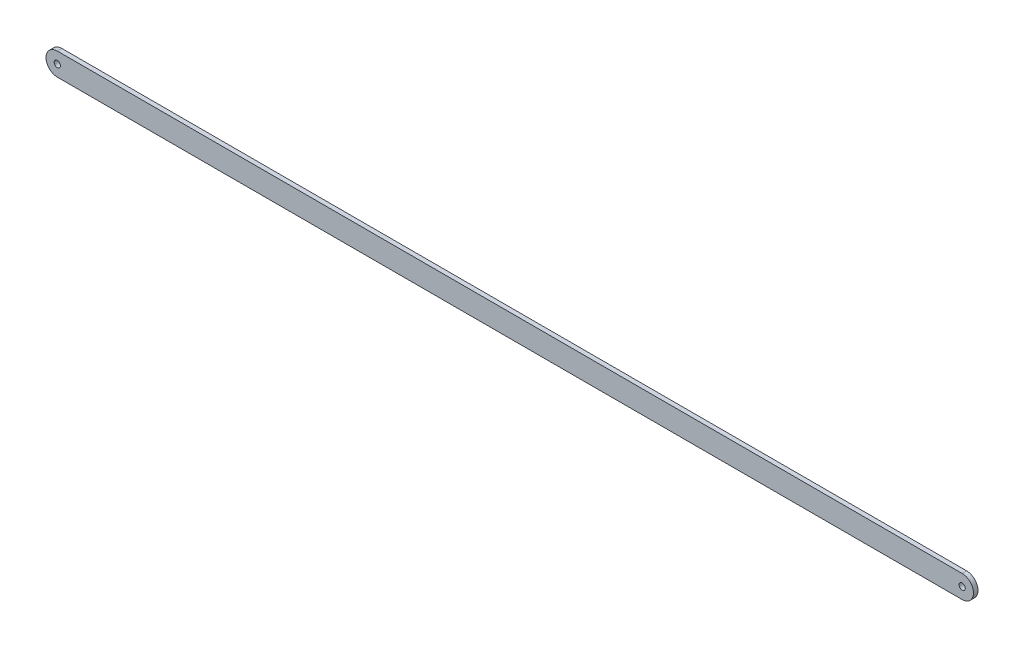
SolidWorks part; units mm, degrees
ref_plane "Front Plane" through (0, 0, 0) normal (0, 0, 1) x (1, 0, 0)
ref_plane "Top Plane" through (0, 0, 0) normal (0, 1, 0) x (1, 0, 0)
ref_plane "Right Plane" through (0, 0, 0) normal (1, 0, 0) x (0, 0, -1)
sketch "Sketch1" plane through (0, 0, 0) normal (0, 0, 1) x (1, 0, 0)
  line L0 (0, 0) -> (0, -50000) construction
  line L1 (-400, -10) -> (400, -10)
  line L2 (-400, -10) -> (-400, 10) construction
  line L3 (-400, 10) -> (400, 10)
  line L4 (400, -10) -> (400, 10) construction
  line L5 (-400, -10) -> (400, 10) construction
  line L6 (-400, 10) -> (400, -10) construction
  arc A0 (-400, 10) -> (-400, -10) centre (-400, 0) ccw
  arc A1 (400, 10) -> (400, -10) centre (400, 0) cw
  circle A2 centre (-400, 0) radius 2.75
  circle A3 centre (400, 0) radius 2.75
  point P0 (0, 0)
  dimension "D3" = 5.5
  dimension "D1" = 20
  dimension "D2" = 800
extrude "Boss-Extrude1" add sketch "Sketch1" along normal blind 4
